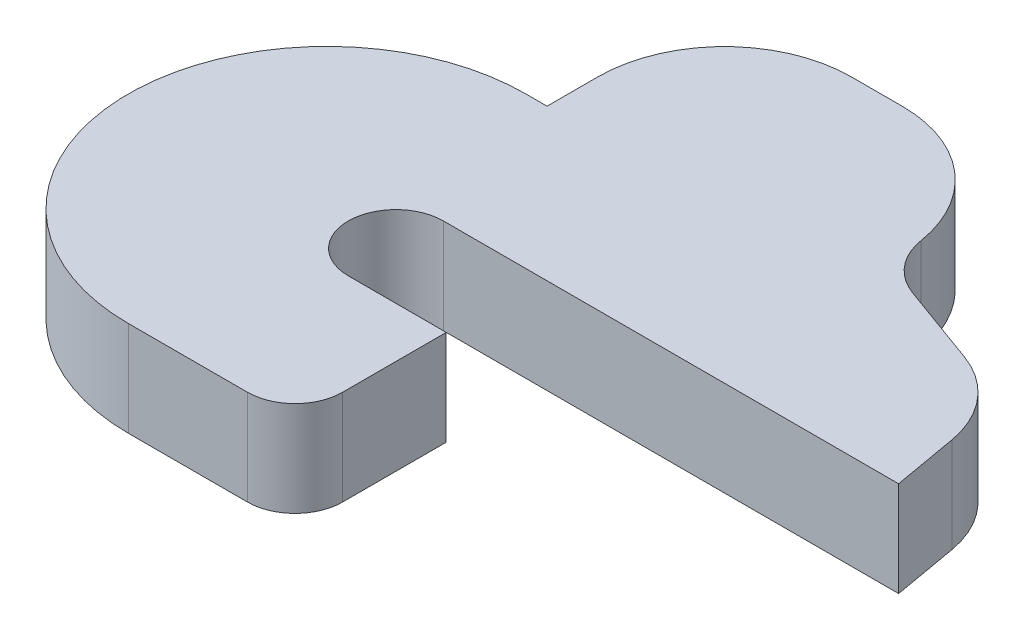
SolidWorks part; units mm, degrees
ref_plane "Front Plane" through (0, 0, 0) normal (0, 0, 1) x (1, 0, 0)
ref_plane "Top Plane" through (0, 0, 0) normal (0, 1, 0) x (1, 0, 0)
ref_plane "Right Plane" through (0, 0, 0) normal (1, 0, 0) x (0, 0, -1)
sketch "Sketch1" plane through (0, 0, 0) normal (0, 1, 0) x (1, 0, 0)
  line L0 (0, 0) -> (-3.09, 0)
  line L1 (-3.09, 3) -> (11.27, 3)
  line L2 (11.27, 3) -> (10.9088, 5.0483)
  line L5 (1.0289, 13.37) -> (-0.59, 13.37)
  line L6 (-4.59, 9.37) -> (-4.59, 7.77)
  line L7 (-4.59, 7.77) -> (-5.26, 7.77)
  line L9 (0, -3.27) -> (0, 0)
  line L10 (-5.26, -4.77) -> (-1.5, -4.77)
  line L11 (6.27, 8.4386) -> (8.851, 7.5)
  arc A0 (-3.09, 0) -> (-3.09, 3) centre (-3.09, 1.5) cw
  arc A1 (10.9088, 5.0483) -> (8.851, 7.5) centre (7.7574, 4.4927) ccw
  arc A4 (-0.59, 13.37) -> (-4.59, 9.37) centre (-0.59, 9.37) ccw
  arc A5 (-5.26, 7.77) -> (-5.26, -4.77) centre (-5.26, 1.5) ccw
  arc A8 (1.0289, 13.37) -> (4.9786, 10.0021) centre (1.0289, 9.37) cw
  arc A9 (6.27, 8.4386) -> (4.9786, 10.0021) centre (6.9535, 10.3182) cw
  arc A10 (-1.5, -4.77) -> (0, -3.27) centre (-1.5, -3.27) ccw
  point P13 (5.0012, 8.9)
  point P43 (-11.53, 1.5)
  point P44 (-4.59, 1.5)
  dimension "D1" = 5.6
  dimension "10.9" = 6.27
  dimension "D4" = 1.5
  dimension "4" = 4
  dimension "3" = 3.2
  dimension "D10" = 2
  dimension "D11" = 1.5
  dimension "D2" = 4
  dimension "D3" = 4.47
  dimension "3.65" = 4.5
  dimension "13.48" = 14.36
  dimension "80" = 80
  dimension "D8" = 6.94
  dimension "D9" = 3.09
  dimension "5" = 5
extrude "Boss-Extrude2" add sketch "Sketch1" along normal blind 3
